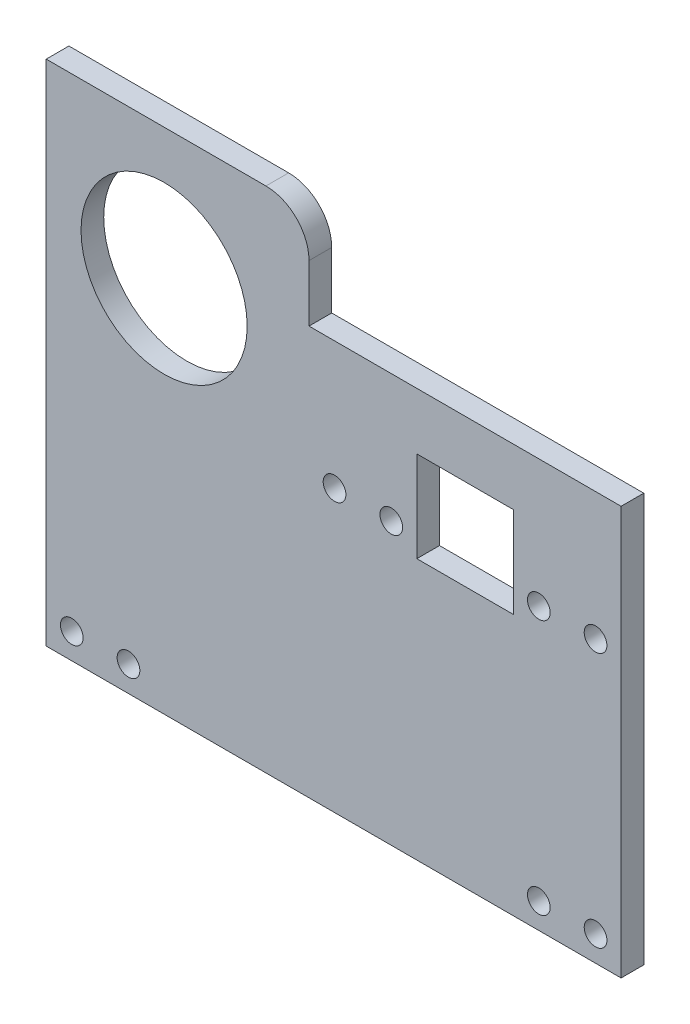
SolidWorks part; units mm, degrees
ref_plane "Front Plane" through (0, 0, 0) normal (0, 0, 1) x (1, 0, 0)
ref_plane "Top Plane" through (0, 0, 0) normal (0, 1, 0) x (1, 0, 0)
ref_plane "Right Plane" through (0, 0, 0) normal (1, 0, 0) x (0, 0, -1)
sketch "Sketch1" plane through (0, 0, 0) normal (0, 0, 1) x (-1, 0, 0)
  line L0 (8.9465, 42.1936) -> (-46.0535, 42.1936)
  line L1 (-46.0535, 42.1936) -> (-46.0535, 114.1936)
  line L2 (-46.0535, 114.1936) -> (55.2632, 114.1936)
  line L3 (55.2632, 24.6016) -> (55.2632, 114.1936)
  line L11 (8.9465, 42.1936) -> (8.9465, 32.1936)
  line L12 (16.5386, 24.6016) -> (55.2632, 24.6016)
  circle A0 centre (34.4865, 47.6716) radius 14.6418
  arc A2 (8.9465, 32.1936) -> (16.5386, 24.6016) centre (16.5386, 32.1936) ccw
  point P0 (34.4865, 15.0477)
  dimension "D7" = 7.592
  dimension "D1" = 72
  dimension "D2" = 55
  dimension "D3" = 25.54
  dimension "D4" = 23.07
  dimension "D5" = 38.7246
  dimension "D8" = 10
extrude "Boss-Extrude1" add sketch "Sketch1" along normal blind 4
sketch "Sketch2" plane through (0, 0, 4) normal (0, 0, 1) x (1, 0, 0)
  line L0 (46.0535, -109.6936) -> (-46.3167, -109.6936) construction
  line L1 (46.0535, -114.1936) -> (46.0535, -42.1936) construction
  line L3 (-4.6048, -114.1936) -> (-4.6048, -64.7728) construction
  line L4 (-55.2632, -114.1936) -> (46.0535, -114.1936) construction
  line L5 (46.0535, -64.6936) -> (3.158, -64.6936) construction
  line L7 (-55.2632, -24.6016) -> (-55.2632, -114.1936) construction
  circle A0 centre (41.5535, -109.6936) radius 2
  circle A1 centre (31.5535, -109.6936) radius 2
  circle A2 centre (-50.7632, -109.6936) radius 2
  circle A3 centre (-40.7632, -109.6936) radius 2
  circle A4 centre (41.5535, -64.6936) radius 2
  circle A5 centre (31.5535, -64.6936) radius 2
  circle A6 centre (-4.4465, -64.6936) radius 2
  circle A7 centre (5.5535, -64.6936) radius 2
  point P31 (-46.3167, -91.6936)
  dimension "D1" = 4
  dimension "D2" = 10
  dimension "D3" = 10
  dimension "D4" = 4.5
  dimension "D5" = 4.5
  dimension "D6" = 45
  dimension "D7" = 4.5
  dimension "D8" = 10
  dimension "D9" = 4.5
  dimension "D10" = 10
  dimension "D11" = 4.5
extrude "Cut-Extrude1" cut sketch "Sketch2" against normal blind 16
sketch "Sketch3" plane through (0, 0, 4) normal (0, 0, 1) x (1, 0, 0)
  line L0 (46.0535, -114.1936) -> (46.0535, -42.1936) construction
  line L1 (10.0535, -52.1936) -> (27.0535, -52.1936)
  line L2 (10.0535, -52.1936) -> (10.0535, -68.1936)
  line L3 (10.0535, -68.1936) -> (27.0535, -68.1936)
  line L4 (27.0535, -52.1936) -> (27.0535, -68.1936)
  line L5 (46.0535, -42.1936) -> (-8.9465, -42.1936) construction
  dimension "D1" = 17
  dimension "D2" = 19
  dimension "D3" = 26
  dimension "D4" = 10
extrude "Cut-Extrude2" cut sketch "Sketch3" against normal blind 7
